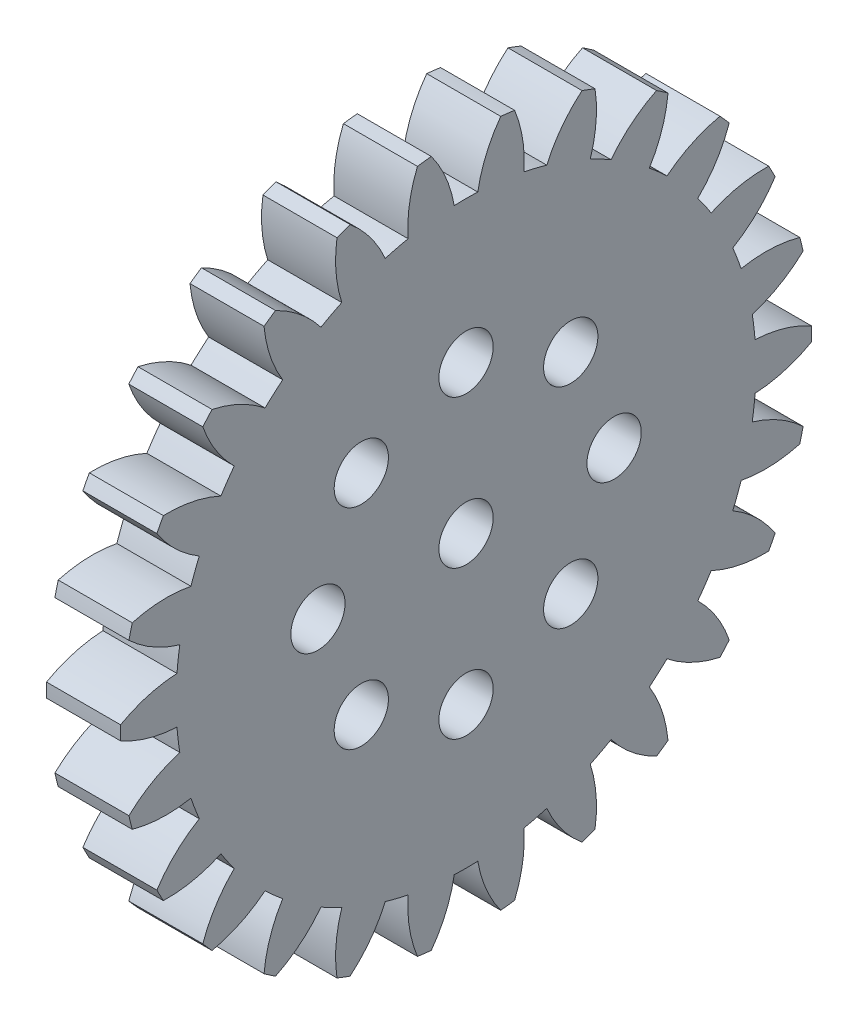
SolidWorks part; units mm, degrees
material "ﾎﾟﾘｵｷｼﾒﾁﾚﾝ(POM)ｱｾﾀｰﾙ共重合体"
ref_plane "Plane1" through (0, 0, 0) normal (0, 0, 1) x (1, 0, 0)
ref_plane "Plane2" through (0, 0, 0) normal (0, 1, 0) x (1, 0, 0)
ref_plane "Plane3" through (0, 0, 0) normal (1, 0, 0) x (0, 0, -1)
other "Configuration Table"
sketch "HoldingSke" plane through (0, 0, 0) normal (0, 1, 0) x (1, 0, 0)
  line L0 (0, 0) -> (0.8988, -0.4384)
  line L1 (-15, 0) -> (100, 0) construction
  line L2 (0, 0) -> (-2.1039, 2.3779)
  line L3 (0, 0) -> (-11.863, 4.5341)
  line L4 (0, 0) -> (7.762, 3.7858)
  line L5 (0, 0) -> (-46.8476, -17.4728)
  line L6 (0, 0) -> (-2.4869, -1.6779)
  line L7 (-2.1039, 2.3779) -> (8.6586, 51.2059)
  line L8 (-76.2, 54.61) -> (-75.2, 54.61)
  line L9 (-71.009, 38.7566) -> (-53.1078, 45.2721)
  line L10 (-76.2, 71.12) -> (104.1128, 71.12)
  line L11 (0, 0) -> (-3, 0)
  line L12 (-76.2, 101.6) -> (-76.162, 101.6)
  line L13 (24.9733, 27.94) -> (52.9518, 28.4284)
  line L14 (24.9733, 27.94) -> (24.9743, 27.94)
  line L15 (24.9733, 27.94) -> (100.4006, 29.5858)
  line L16 (-63.627, -1) -> (-12.827, -1)
  circle A0 centre (0, 0) radius 4
  circle A1 centre (0, 0) radius 11.749
  circle A2 centre (0, 0) radius 37.5
  circle A3 centre (0, 0) radius 4
  dimension "MHD" = 23.498
  dimension "Hub_dia" = 75
  dimension "Bore" = 8
  dimension "MBD" = 8
  dimension "Num_teeth" = 26
  dimension "Pitch" = 1
  dimension "Overall_len" = 50
  dimension "Show_teeth" = 26
  dimension "Thickness" = 3
  dimension "OAL" = 50.0001
  dimension "T_dim" = 1
  dimension "Ap" = 20
  dimension "H" = 19.05
  dimension "Pitch_radius" = 180.3128
  dimension "Width" = 3
  dimension "Backlash" = 0.038
  dimension "Addendum_fac" = 1
  dimension "Dedendum_fac" = 1.25
  dimension "Clearance_fac" = 0.25
  dimension "Dedendum_add" = 0.001
  dimension "Module" = 1
sketch "BasProSke" plane through (0, 0, 0) normal (0, 1, 0) x (1, 0, 0)
  line L0 (-10, 0) -> (60, 0) construction
  line L1 (0, 0) -> (0, 14)
  line L2 (0, 0) -> (3, 0)
  line L3 (3, 0) -> (3, 14)
  line L4 (3, 14) -> (0, 14)
  dimension "Thickness" = 3
  dimension "Diameter" = 28
revolve "Base-Revolve" add sketch "BasProSke" angle 360 about L0
sketch "TooCutSke" plane through (0, 0, 0) normal (1, 0, 0) x (0, 0, -1)
  line L1 (0, 0) -> (0, 107) construction
  line L2 (0, 0) -> (-0.8514, 12.9721) construction
  line L3 (0, 0) -> (-3.1292, 25.771) construction
  line L4 (-0.8514, 12.9721) -> (-1.5646, 12.8855) construction
  arc A0 (0.477, 11.7393) -> (-0.477, 11.7393) centre (0, 0) ccw
  arc A1 (1.4241, 13.9529) -> (-1.4241, 13.9529) centre (0, 0) ccw
  circle A2 centre (0, 0) radius 13 construction
  circle A3 centre (0, 0) radius 12.216 construction
  arc A4 (-0.477, 11.7393) -> (-1.4241, 13.9529) centre (-5.6014, 10.8561) ccw
  arc A5 (1.4241, 13.9529) -> (0.477, 11.7393) centre (5.6014, 10.8561) ccw
  dimension "Root_dia" = 23.498
  dimension "Overcut_dia" = 28.0508
  dimension "Pitch_dia" = 26
  dimension "Base_dia" = 24.432
  dimension "Flank_rad" = 5.2
  dimension "Half_ang" = 6.923
  dimension "Half_CT" = 0.7184
extrude "ToothCut" cut sketch "TooCutSke" along normal through all
fillet "Breaks" [suppressed] radius 0.02
fillet "RootFillets" [suppressed] radius 0.251
pattern_circular "TeethCuts" count 26 every 13.846 about axis through (-10, 0, 0) along (1, 0, 0) of "ToothCut", "RootFillets", "Breaks"
sketch "HubNeaOneSke" plane through (0, 0, 0) normal (-1, 0, 0) x (0, 0, 1)
  circle A0 centre (0, 0) radius 11.749
  dimension "Diameter" = 23.498
extrude "HubNearOne" [suppressed] add sketch "HubNeaOneSke" along normal blind 47.0001
sketch "HubNeaBotSke" plane through (0, 0, 0) normal (-1, 0, 0) x (0, 0, 1)
  circle A0 centre (0, 0) radius 11.749
  dimension "Diameter" = 23.498
extrude "HubNearBoth" [suppressed] add sketch "HubNeaBotSke" along normal blind 23.5
ref_plane "FarPln" through (3, 0, 0) normal (1, 0, 0) x (0, 0, -1)
sketch "HubFarSke" plane through (3, 0, 0) normal (1, 0, 0) x (0, 0, -1)
  circle A0 centre (0, 0) radius 11.749
  dimension "Diameter" = 23.498
extrude "HubFar" [suppressed] add sketch "HubFarSke" along normal blind 23.5
sketch "BorSke" plane through (0, 0, 0) normal (1, 0, 0) x (0, 0, -1)
  circle A0 centre (0, 0) radius 4
  dimension "Diameter" = 8
extrude "Bore" cut sketch "BorSke" along normal mid plane 100.0001
sketch "KeySke" plane through (0, 0, 0) normal (1, 0, 0) x (0, 0, -1)
  line L0 (-1, 0) -> (-1, 5)
  line L1 (-1, 5) -> (1, 5)
  line L2 (1, 5) -> (1, 0)
  line L3 (0, 0) -> (0, 34) construction
  line L4 (-1, 0) -> (1, 0)
  dimension "Offset" = 5
  dimension "Width" = 2
extrude "Keyway" [suppressed] cut sketch "KeySke" along normal mid plane 100.0001
pattern_circular "Keyway2" [suppressed] count 2 every 90 about axis through (-10, 0, 0) along (1, 0, 0)
sketch "ｽｹｯﾁ1" plane through (0, 0, 0) normal (-1, 0, 0) x (0, 0, 1)
  circle A0 centre (0, 0) radius 4
  dimension "D1" = 8
extrude "ﾎﾞｽ - 押し出し1" add sketch "ｽｹｯﾁ1" against normal up to surface (3 mm away) up to face at (3, 0, 4)
sketch "ｽｹｯﾁ2" plane through (0, 0, 0) normal (-1, 0, 0) x (0, 0, 1)
  circle A0 centre (0, 0) radius 6 construction
  circle A1 centre (0, 0) radius 1.1
  circle A2 centre (0, 6) radius 1.1
  circle A3 centre (4.2426, 4.2426) radius 1.1
  circle A4 centre (6, 0) radius 1.1
  circle A5 centre (4.2426, -4.2426) radius 1.1
  circle A6 centre (0, -6) radius 1.1
  circle A7 centre (-4.2426, -4.2426) radius 1.1
  circle A8 centre (-6, 0) radius 1.1
  circle A9 centre (-4.2426, 4.2426) radius 1.1
  point P6 (0, 0)
  point P23 (0, 0)
  dimension "D1" = 2.2
  dimension "D2" = 12
  dimension "D3" = 2.2
extrude "ｶｯﾄ - 押し出し1" cut sketch "ｽｹｯﾁ2" against normal up to surface (3 mm away) up to face at (3, 0, 0)
equation "' \"Module@HoldingSke\" = 6.35"
equation "' \"Num_teeth@HoldingSke\" = 12"
equation "' \"Ap@HoldingSke\" =  20"
equation "' \"Ap@HoldingSke\" = 20"
equation "' \"Width@HoldingSke\" = 0.5 * 25.4"
equation "' \"Hub_dia@HoldingSke\"= 1 * 25.4"
equation "' \"Hub_dia@HoldingSke\" = 1 * 25.4"
equation "' \"Overall_len@HoldingSke\" = 1.0 * 25.4"
equation "' \"Bore@HoldingSke\" = 0.75 * 25.4"
equation "' \"T_dim@HoldingSke\" = 0.1 * 25.4"
equation "' \"Width@KeySke\" = 0.25 * 25.4"
equation "' \"Show_teeth@HoldingSke\" = 13"
equation "' \"Backlash@HoldingSke\" = 0.009 * 25.4"
equation "' \"Addendum_fac@HoldingSke\" = 1.0"
equation "' \"Dedendum_fac@HoldingSke\" = 1.25"
equation "' \"Dedendum_add@HoldingSke\" = 0.00005 * 25.4"
equation "' \"Clearance_fac@HoldingSke\" = 0.25"
equation "\"Pitch@HoldingSke\" = 1 / \"Module@HoldingSke\""
equation "\"Overcut_dia@TooCutSke\" = (\"Num_teeth@HoldingSke\" + 2 * \"Addendum_fac@HoldingSke\") / \"Pitch@HoldingSke\" + 0.002 * 25.4"
equation "\"Pitch_dia@TooCutSke\" = \"Num_teeth@HoldingSke\" / \"Pitch@HoldingSke\""
equation "\"Base_dia@TooCutSke\" = \"Num_teeth@HoldingSke\" / \"Pitch@HoldingSke\" * cos((\"Ap@HoldingSke\"  * 3.14159265 / 180))"
equation "\"Root_dia@TooCutSke\" = (\"Num_teeth@HoldingSke\" + 2) / \"Pitch@HoldingSke\" - 2 * (\"Addendum_fac@HoldingSke\" + \"Dedendum_fac@HoldingSke\") / \"Pitch@HoldingSke\" - \"Dedendum_add@HoldingSke\" * 2"
equation "\"Half_ang@TooCutSke\" = 180 / \"Num_teeth@HoldingSke\""
equation "\"Half_CT@TooCutSke\" = \"Num_teeth@HoldingSke\" / \"Pitch@HoldingSke\" * sin((3.14159265 / 2 / \"Num_teeth@HoldingSke\")) / 2 - 7 * \"Backlash@HoldingSke\" / 4"
equation "\"Flank_rad@TooCutSke\" = \"Num_teeth@HoldingSke\" / \"Pitch@HoldingSke\" / 5"
equation "\"Radius@RootFillets\" = \"Clearance_fac@HoldingSke\" / \"Pitch@HoldingSke\" + \"Dedendum_add@HoldingSke\""
equation "\"Break_rad@Breaks\" = 0.02 / \"Pitch@HoldingSke\""
equation "\"Thickness@HoldingSke\" = \"Width@HoldingSke\""
equation "\"OAL@HoldingSke\" = \"Thickness@HoldingSke\""
equation "\"MHD@HoldingSke\" = (\"Num_teeth@HoldingSke\" + 2) / \"Pitch@HoldingSke\" - 2 * (\"Addendum_fac@HoldingSke\" + \"Dedendum_fac@HoldingSke\")  / \"Pitch@HoldingSke\" - \"Dedendum_add@HoldingSke\" * 2"
equation "\"MBD@HoldingSke\" = (\"Num_teeth@HoldingSke\" + 2) / \"Pitch@HoldingSke\" - 2 * (\"Addendum_fac@HoldingSke\" + \"Dedendum_fac@HoldingSke\")  / \"Pitch@HoldingSke\" - \"Dedendum_add@HoldingSke\" * 2 - 0.002 * 25.4"
equation "\"MHD@HoldingSke\" = ((sgn( \"MHD@HoldingSke\" - \"Hub_dia@HoldingSke\" )-1)*( \"MHD@HoldingSke\" - \"Hub_dia@HoldingSke\" ))/-2+ \"Hub_dia@HoldingSke\""
equation "\"MBD@HoldingSke\" = ((sgn( \"MBD@HoldingSke\" - \"Bore@HoldingSke\" )-1)*( \"MBD@HoldingSke\" - \"Bore@HoldingSke\" ))/-2+ \"Bore@HoldingSke\""
equation "\"OAL@HoldingSke\" = ((sgn( \"OAL@HoldingSke\" - \"Overall_len@HoldingSke\" )+1)*( \"OAL@HoldingSke\" - \"Overall_len@HoldingSke\" ))/2 + \"Overall_len@HoldingSke\" + 0.000002 * 25.4"
equation "\"Num_teeth@TeethCuts\" = int( \"Show_teeth@HoldingSke\" ) + 1"
equation "\"Num_teeth@TeethCuts\" = ((sgn( \"Num_teeth@TeethCuts\" - \"Num_teeth@HoldingSke\" )-1)*( \"Num_teeth@TeethCuts\" - \"Num_teeth@HoldingSke\" ))/-2+ \"Num_teeth@HoldingSke\""
equation "\"Num_teeth@TeethCuts\" = ((sgn( \"Num_teeth@TeethCuts\" - 2.0)+1)*( \"Num_teeth@TeethCuts\" - 2.0))/2 +2.0"
equation "\"Angle@TeethCuts\" = 360.0 / \"Num_teeth@HoldingSke\""
equation "\"Diameter@BasProSke\" = (\"Num_teeth@HoldingSke\" + 2 * \"Addendum_fac@HoldingSke\") / \"Pitch@HoldingSke\""
equation "\"Thickness@BasProSke\"  = \"Thickness@HoldingSke\""
equation "' \"Fillet_rad@BasProSke\" =  \"Thickness@HoldingSke\" * 0.05"
equation "' \"Fillet_rad@BasProSke\" = \"Thickness@HoldingSke\" * 0.05"
equation "\"MHD@HoldingSke\" = ((sgn( \"MHD@HoldingSke\" - \"Root_dia@TooCutSke\" )-1)*( \"MHD@HoldingSke\" - \"Root_dia@TooCutSke\" ))/-2+ \"Root_dia@TooCutSke\""
equation "\"Diameter@HubNeaOneSke\" = \"MHD@HoldingSke\""
equation "\"Length@HubNearOne\" = \"OAL@HoldingSke\" - \"Thickness@BasProSke\""
equation "\"Diameter@HubNeaBotSke\" = \"MHD@HoldingSke\""
equation "\"Length@HubNearBoth\" = ( \"OAL@HoldingSke\" - \"Thickness@BasProSke\" ) / 2.0"
equation "\"Thickness@FarPln\" = \"Thickness@BasProSke\""
equation "\"Diameter@HubFarSke\" = \"MHD@HoldingSke\""
equation "\"Length@HubFar\" = ( \"OAL@HoldingSke\" - \"Thickness@BasProSke\" ) / 2.0"
equation "\"Diameter@BorSke\" = \"MBD@HoldingSke\""
equation "\"D1@Bore\" = \"OAL@HoldingSke\" * 2.0"
equation "\"D1@Keyway\" = \"OAL@HoldingSke\" * 2.0"
equation "\"Offset@KeySke\" = \"T_dim@HoldingSke\" + \"MBD@HoldingSke\" / 2.0"
